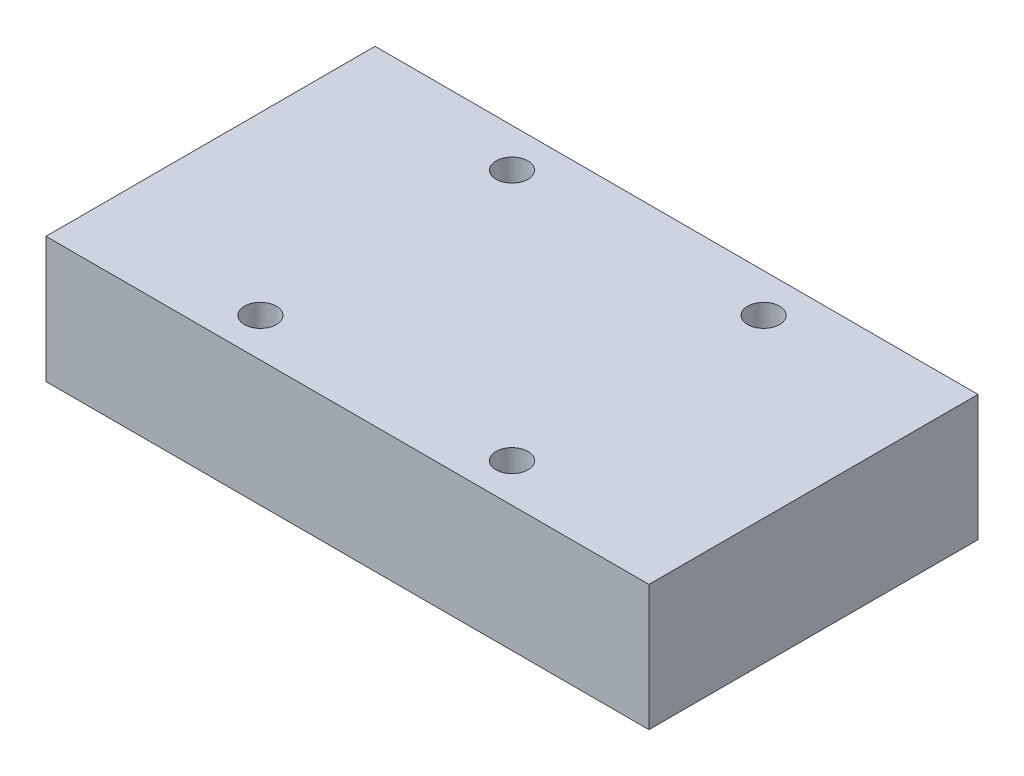
SolidWorks part; units mm, degrees
ref_plane "前视基准面" through (0, 0, 0) normal (0, 0, 1) x (1, 0, 0)
ref_plane "上视基准面" through (0, 0, 0) normal (0, 1, 0) x (1, 0, 0)
ref_plane "右视基准面" through (0, 0, 0) normal (1, 0, 0) x (0, 0, -1)
sketch "草图1" plane through (0, 0, 0) normal (0, 1, 0) x (1, 0, 0)
  line L1 (-31.15, 17) -> (31.15, 17)
  line L2 (-31.15, 17) -> (-31.15, -17)
  line L3 (-31.15, -17) -> (31.15, -17)
  line L4 (31.15, 17) -> (31.15, -17)
  line L5 (-31.15, 17) -> (31.15, -17) construction
  line L6 (-31.15, -17) -> (31.15, 17) construction
  point P0 (0, 0)
  dimension "D1" = 34
  dimension "D2" = 62.3
extrude "主体" add sketch "草图1" along normal blind 13
sketch "草图2" plane through (0, 13, 0) normal (0, 1, 0) x (1, 0, 0)
  line L1 (-13, 13) -> (13, 13) construction
  line L2 (-13, 13) -> (-13, -13) construction
  line L3 (-13, -13) -> (13, -13) construction
  line L4 (13, 13) -> (13, -13) construction
  line L5 (-13, 13) -> (13, -13) construction
  line L6 (-13, -13) -> (13, 13) construction
  point P0 (0, 0)
  point P6 (0, 0)
  dimension "D1" = 26
  dimension "D2" = 26
hole_wizard "M4 螺纹孔1" positions "草图5" profile "草图6" tap size "M4" standard "ISO"
sketch "草图5" plane through (0, 13, 0) normal (0, 1, 0) x (1, 0, 0)
  point P0 (-13, 13)
  point P2 (-13, -13)
  point P4 (13, 13)
  point P6 (13, -13)
  point P9 (0, 0)
  point P11 (0, 0)
  point P14 (0, 0)
sketch "草图6" plane through (-13, 13, -13) normal (1, 0, 0) x (0, 0, 1)
  line L0 (0, 0) -> (0, 5.9914)
  line L1 (0, 5.9914) -> (1.65, 5)
  line L2 (1.65, 5) -> (1.65, 0)
  line L5 (1.65, 0) -> (0, 0)
  line L10 (0, 5.9914) -> (-1.65, 5) construction
  line L11 (0, -6.35) -> (0, 107.95) construction
  dimension "螺纹孔钻头直径" = 3.3
  dimension "螺纹孔钻头深度" = 5
  dimension "导头角度" = 118
cosmetic thread "孔螺蚊线5" parameters "D1"=5, "D2"=4
cosmetic thread "孔螺蚊线6" parameters "D1"=5, "D2"=4
cosmetic thread "孔螺蚊线7" parameters "D1"=5, "D2"=4
cosmetic thread "孔螺蚊线8" parameters "D1"=5, "D2"=4
